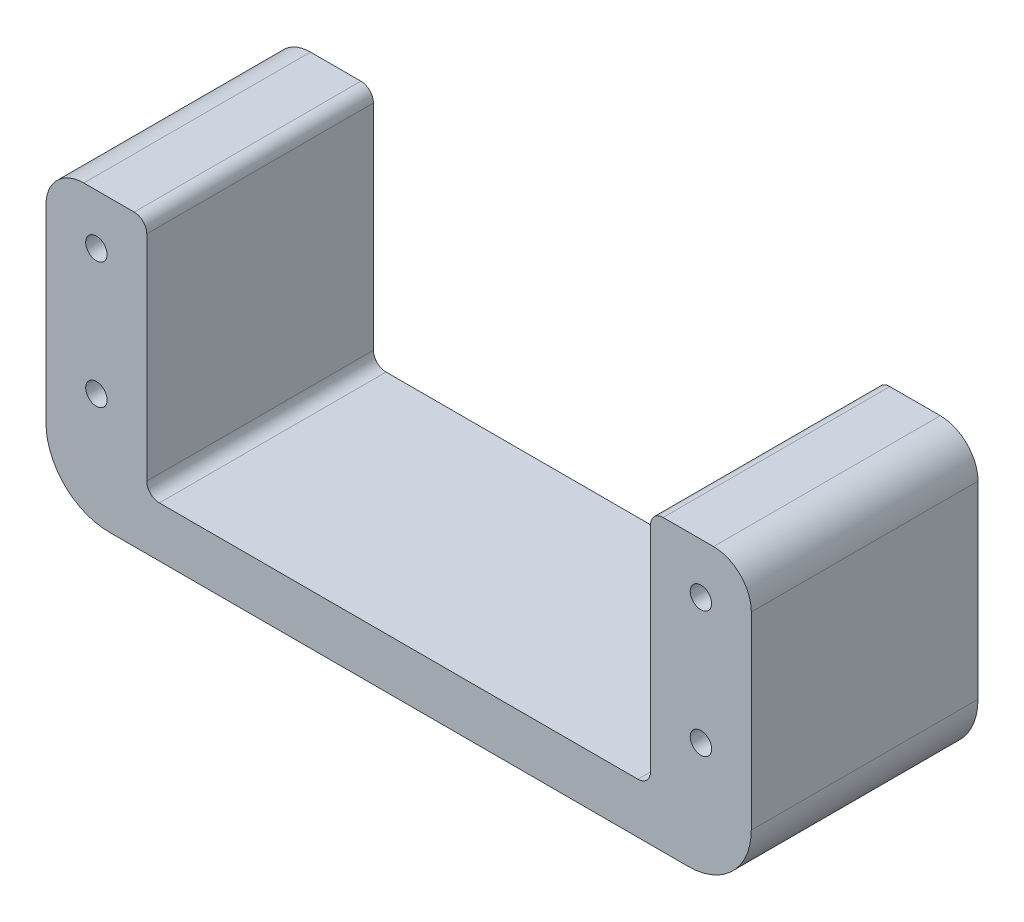
SolidWorks part; units mm, degrees
material "ABS"
ref_plane "Front" through (0, 0, 0) normal (0, 0, 1) x (1, 0, 0)
ref_plane "Top" through (0, 0, 0) normal (0, 1, 0) x (1, 0, 0)
ref_plane "Right" through (0, 0, 0) normal (1, 0, 0) x (0, 0, -1)
sketch "Esquisse1" plane through (0, 0, 0) normal (0, 0, 1) x (1, 0, 0)
  line L0 (20, 23) -> (28, 23)
  line L1 (-28, 23) -> (-20, 23)
  line L2 (-28, 23) -> (-28, 0)
  line L3 (-28, 0) -> (28, 0)
  line L4 (28, 23) -> (28, 0)
  line L6 (-20, 23) -> (-20, 4)
  line L7 (-20, 4) -> (20, 4)
  line L8 (20, 23) -> (20, 4)
  line L9 (0, -50) -> (0, 50) construction
  circle A0 centre (-24, 19) radius 0.85
  circle A1 centre (-24, 9) radius 0.85
  circle A2 centre (24, 9) radius 0.85
  circle A3 centre (24, 19) radius 0.85
  dimension "D1" = 10
  dimension "D2" = 48
  dimension "D6" = 5
  dimension "D7" = 1.7
  dimension "D9" = 4
  dimension "D3" = 40
  dimension "D4" = 4
  dimension "D5" = 4
  dimension "D8" = 56
  dimension "D10" = 8
  dimension "D11" = 23
extrude "Boss.-Extru.1" add sketch "Esquisse1" along normal blind 18
fillet "Congé1" radius 1 4 edges at (20, 23, 9) (-20, 23, 9) (20, 4, 9) (-20, 4, 9)
fillet "Congé2" radius 3 2 edges at (28, 23, 9) (-28, 23, 9)
fillet "Congé3" radius 5 2 edges at (-28, 0, 9) (28, 0, 9)
sketch "Esquisse4" plane through (0, 0, 18) normal (0, 0, 1) x (1, 0, 0)
  line L8 (-28, 20) -> (-28, 5)
  line L9 (-23, 0) -> (23, 0)
  line L10 (28, 5) -> (28, 20)
  line L11 (25, 23) -> (21, 23)
  line L12 (20, 22) -> (20, 5)
  line L13 (19, 4) -> (-19, 4)
  line L14 (-20, 5) -> (-20, 22)
  line L15 (-21, 23) -> (-25, 23)
  line L16 (-28, 20) -> (-28, 5)
  line L17 (-23, 0) -> (23, 0)
  line L18 (28, 5) -> (28, 20)
  line L23 (25, 23) -> (-25, 23)
  arc A8 (-28, 5) -> (-23, 0) centre (-23, 5) ccw
  arc A9 (23, 0) -> (28, 5) centre (23, 5) ccw
  arc A10 (28, 20) -> (25, 23) centre (25, 20) ccw
  arc A11 (21, 23) -> (20, 22) centre (21, 22) ccw
  arc A12 (19, 4) -> (20, 5) centre (19, 5) ccw
  arc A13 (-20, 5) -> (-19, 4) centre (-19, 5) ccw
  arc A14 (-20, 22) -> (-21, 23) centre (-21, 22) ccw
  arc A15 (-25, 23) -> (-28, 20) centre (-25, 20) ccw
  arc A16 (-28, 5) -> (-23, 0) centre (-23, 5) ccw
  arc A18 (28, 20) -> (25, 23) centre (25, 20) ccw
  arc A23 (-25, 23) -> (-28, 20) centre (-25, 20) ccw
  arc A24 (23, 0) -> (28, 5) centre (23, 5) ccw
  point P5 (13.332, 23)
  dimension "D1" = 0
extrude "Boss.-Extru.3" [suppressed] add sketch "Esquisse4" against normal blind 0.2
